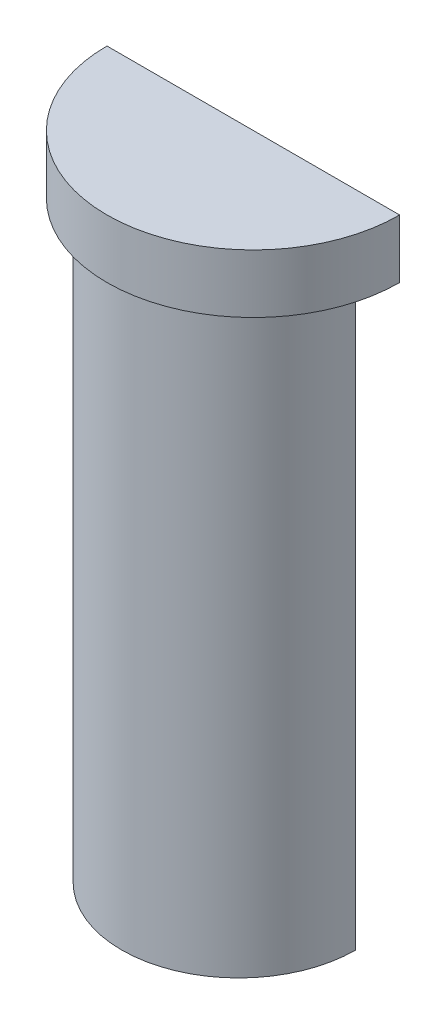
SolidWorks part; units mm, degrees
ref_plane "前视基准面" through (0, 0, 0) normal (0, 0, 1) x (1, 0, 0)
ref_plane "上视基准面" through (0, 0, 0) normal (0, 1, 0) x (1, 0, 0)
ref_plane "右视基准面" through (0, 0, 0) normal (1, 0, 0) x (0, 0, -1)
other "Configuration Table"
sketch "草图1" plane through (0, 0, 0) normal (0, 1, 0) x (1, 0, 0)
  line L0 (0, 0) -> (4, 0)
  arc A0 (0, 0) -> (4, 0) centre (2, 0) ccw
  dimension "D1" = 4
extrude "凸台-拉伸1" add sketch "草图1" along normal mid plane 10
ref_plane "基准面1" through (0, 5, 0) normal (0, 1, 0) x (1, 0, 0)
sketch "草图2" plane through (0, 5, 0) normal (0, 1, 0) x (1, 0, 0)
  line L0 (4, 0) -> (0, 0) construction
  line L3 (-0.5, 0.25) -> (4.5, 0.25)
  arc A0 (-0.5, 0.25) -> (4.5, 0.25) centre (2, 0.25) ccw
  arc A1 (0, 0) -> (4, 0) centre (2, 0) ccw construction
  point P9 (2, -2)
  point P10 (2, -2.25)
  dimension "D1" = 0.25
  dimension "D2" = 0.25
extrude "凸台-拉伸2" add sketch "草图2" along normal blind 1
